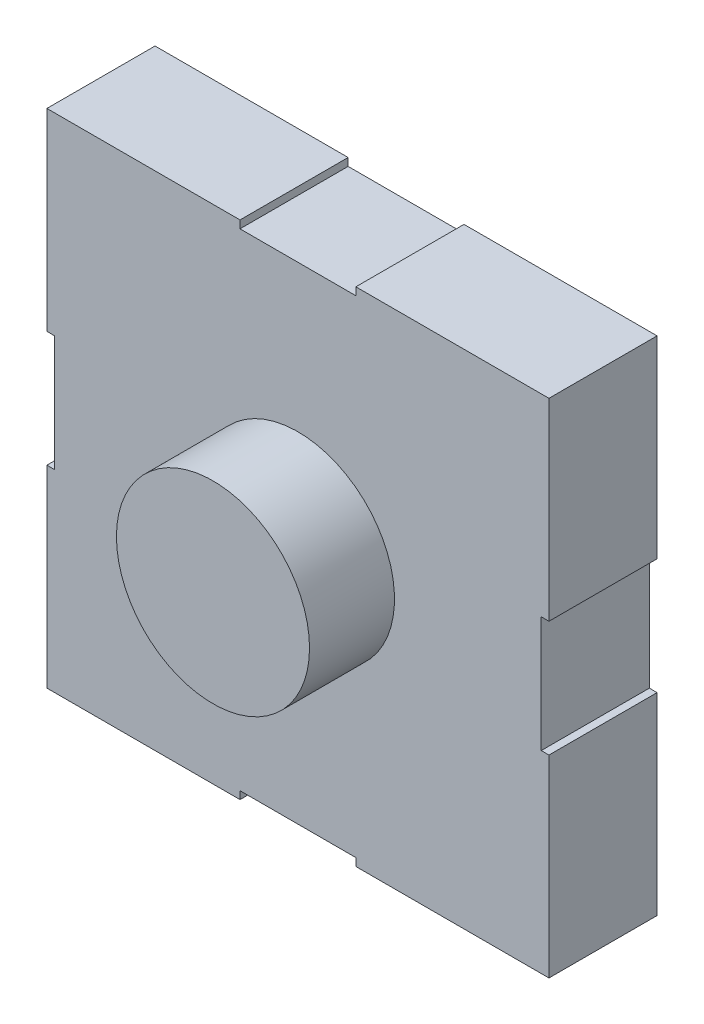
SolidWorks part; units mm, degrees
ref_plane "Plan de face" through (0, 0, 0) normal (0, 0, 1) x (1, 0, 0)
ref_plane "Plan de dessus" through (0, 0, 0) normal (0, 1, 0) x (1, 0, 0)
ref_plane "Plan de droite" through (0, 0, 0) normal (1, 0, 0) x (0, 0, -1)
sketch "Esquisse1" plane through (0, 0, 0) normal (0, 0, 1) x (1, 0, 0)
  line L0 (-3.25, 0.75) -> (-3.25, 3.25)
  line L1 (-3.25, -3.25) -> (-0.75, -3.25)
  line L2 (-3.25, -3.25) -> (-3.25, -0.75)
  line L3 (-3.25, 3.25) -> (-0.75, 3.25)
  line L4 (3.25, -3.25) -> (3.25, -0.75)
  line L5 (-3.25, -3.25) -> (3.25, 3.25) construction
  line L6 (-3.25, 3.25) -> (3.25, -3.25) construction
  line L7 (-3.25, -0.75) -> (-3.15, -0.75)
  line L8 (-0.75, 3.15) -> (0.75, 3.15)
  line L9 (-3.25, 0.75) -> (-3.15, 0.75)
  line L10 (-3.15, -0.75) -> (-3.15, 0.75)
  line L11 (0.75, 3.25) -> (0.75, 3.15)
  line L12 (-0.75, 3.25) -> (-0.75, 3.15)
  line L13 (3.15, 0.75) -> (3.15, -0.75)
  line L14 (3.25, -0.75) -> (3.15, -0.75)
  line L15 (3.25, 0.75) -> (3.15, 0.75)
  line L16 (0.75, -3.15) -> (-0.75, -3.15)
  line L17 (-0.75, -3.25) -> (-0.75, -3.15)
  line L18 (0.75, -3.25) -> (0.75, -3.15)
  line L19 (0.75, 3.25) -> (3.25, 3.25)
  line L20 (3.25, 0.75) -> (3.25, 3.25)
  line L21 (0.75, -3.25) -> (3.25, -3.25)
  point P0 (0, 0)
  point P14 (0, 0)
  point P19 (0, 0)
  point P24 (0, 0)
  point P29 (0, 0)
  dimension "D2" = 6.5
  dimension "D3" = 4
extrude "Boss.-Extru.1" add sketch "Esquisse1" along normal blind 1.4
sketch "Esquisse2" plane through (0, 0, 1.4) normal (0, 0, 1) x (1, 0, 0)
  circle A0 centre (0, 0) radius 1.25
  dimension "D1" = 2.5
extrude "Boss.-Extru.2" add sketch "Esquisse2" along normal blind 1.1
